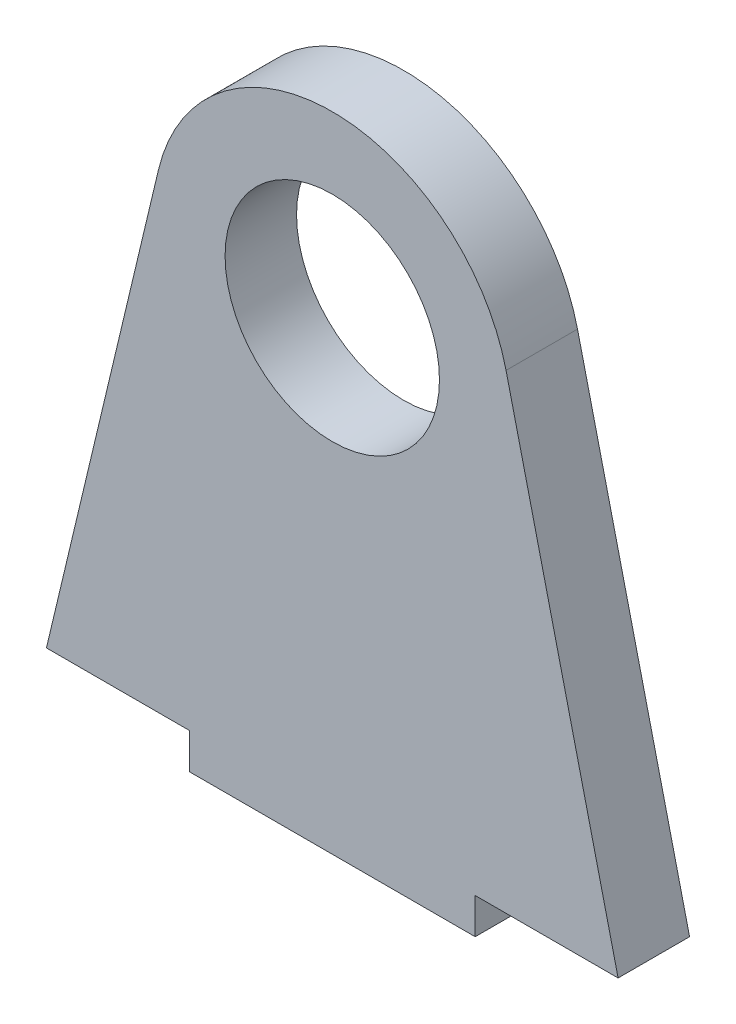
SolidWorks part; units mm, degrees
material "Mahogany"
ref_plane "Front Plane" through (0, 0, 0) normal (0, 0, 1) x (1, 0, 0)
ref_plane "Top Plane" through (0, 0, 0) normal (0, 1, 0) x (1, 0, 0)
ref_plane "Right Plane" through (0, 0, 0) normal (1, 0, 0) x (0, 0, -1)
sketch "Sketch1" plane through (0, 0, 0) normal (0, 0, 1) x (1, 0, 0)
  line L0 (0, 16.25) -> (0, -16.25) construction
  line L1 (-17.1699, -16.25) -> (17.1699, -16.25) construction
  line L2 (-20, -13.75) -> (20, -13.75) construction
  line L3 (12.1594, 19.148) -> (20, -13.75)
  line L4 (-12.1594, 19.148) -> (-20, -13.75)
  line L5 (20, -13.75) -> (10, -13.75)
  line L6 (10, -13.75) -> (10, -16.25)
  line L7 (10, -16.25) -> (-10, -16.25)
  line L8 (-10, -13.75) -> (-10, -16.25)
  line L9 (-20, -13.75) -> (-10, -13.75)
  arc A0 (-12.1594, 19.148) -> (12.1594, 19.148) centre (0, 16.25) cw
  circle A1 centre (0, 16.25) radius 7.5
  dimension "D2" = 15
  dimension "D3" = 12.5
  dimension "D1" = 2.5
  dimension "D4" = 30
  dimension "D5" = 40
  dimension "D6" = 20
extrude "Boss-Extrude1" add sketch "Sketch1" along normal blind 5
